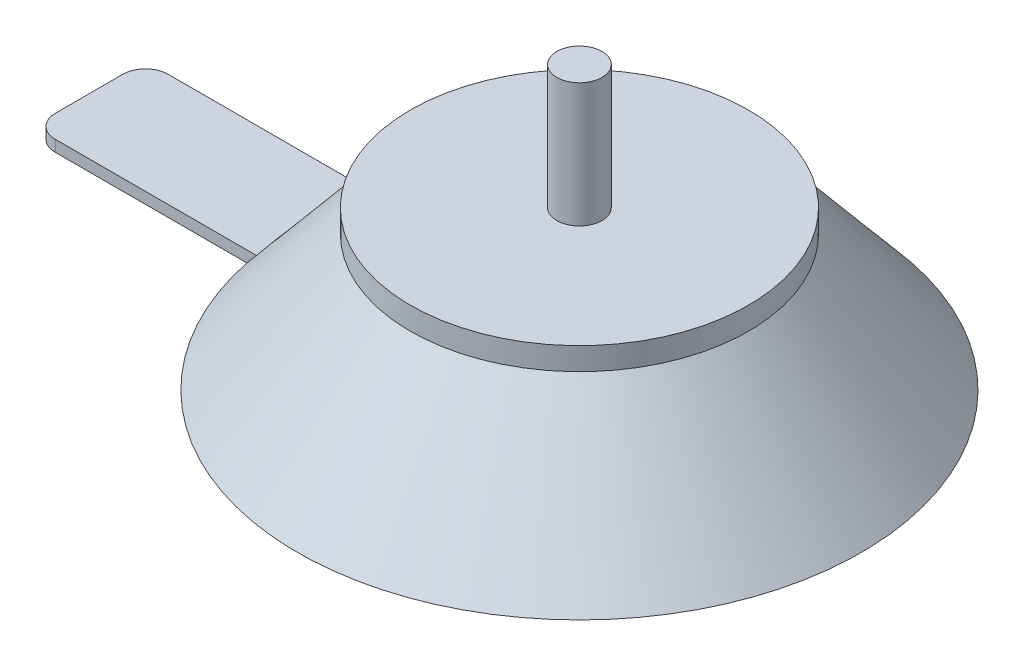
SolidWorks part; units mm, degrees
ref_plane "Front Plane" through (0, 0, 0) normal (0, 0, 1) x (1, 0, 0)
ref_plane "Top Plane" through (0, 0, 0) normal (0, 1, 0) x (1, 0, 0)
ref_plane "Right Plane" through (0, 0, 0) normal (1, 0, 0) x (0, 0, -1)
sketch "Sketch1" plane through (0, 0, 0) normal (0, 0, 1) x (1, 0, 0)
  line L0 (0, 0) -> (-25, 0)
  line L1 (-25, 0) -> (-15, 12)
  line L2 (-15, 12) -> (-15, 14)
  line L3 (-15, 14) -> (-2, 14)
  line L4 (-2, 14) -> (-2, 25)
  line L5 (-2, 25) -> (0, 25)
  line L6 (0, 25) -> (0, 0)
  dimension "D1" = 25
  dimension "D2" = 15
  dimension "D3" = 11
  dimension "D4" = 25
  dimension "D5" = 2
  dimension "D6" = 2
revolve "Revolve1" add sketch "Sketch1" angle 360 about L6
sketch "Sketch2" plane through (0, 0, 0) normal (0, -1, 0) x (1, 0, 0)
  line L0 (-24.4949, 5) -> (-43.4949, 5)
  line L1 (-43.4949, 5) -> (-43.4949, -5)
  line L2 (-43.4949, -5) -> (-24.4949, -5)
  line L3 (-43.4949, 0) -> (-36.8406, 0) construction
  line L4 (-24.4949, 5) -> (-19.5959, 5)
  line L5 (-19.5959, 5) -> (-19.5959, -5)
  line L6 (-19.5959, -5) -> (-24.4949, -5)
  circle A0 centre (0, 0) radius 25 construction
  dimension "D1" = 19
  dimension "D2" = 10
extrude "Boss-Extrude1" add sketch "Sketch2" against normal blind 1
fillet "Fillet1" radius 2 2 edges at (-43.4949, 0.5, -5) (-43.4949, 0.5, 5)
